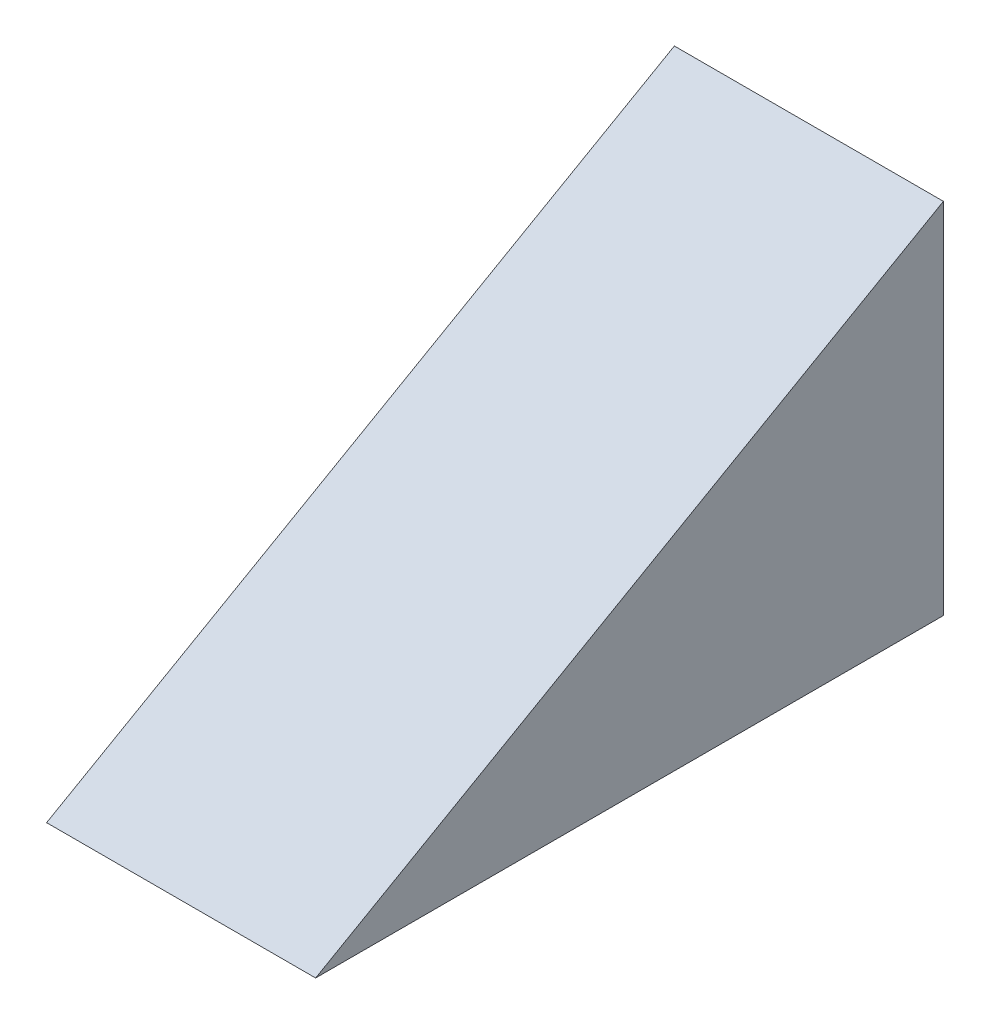
SolidWorks part; units mm, degrees
ref_plane "Front Plane" through (0, 0, 0) normal (0, 0, 1) x (1, 0, 0)
ref_plane "Top Plane" through (0, 0, 0) normal (0, 1, 0) x (1, 0, 0)
ref_plane "Right Plane" through (0, 0, 0) normal (1, 0, 0) x (0, 0, -1)
sketch "Sketch1" plane through (0, 0, 0) normal (1, 0, 0) x (0, 0, -1)
  line L0 (0, 0) -> (35, 0)
  line L1 (35, 0) -> (35, 20)
  line L2 (35, 20) -> (0, 0)
  dimension "D1" = 20
  dimension "D2" = 35
extrude "Boss-Extrude1" add sketch "Sketch1" along normal blind 15
